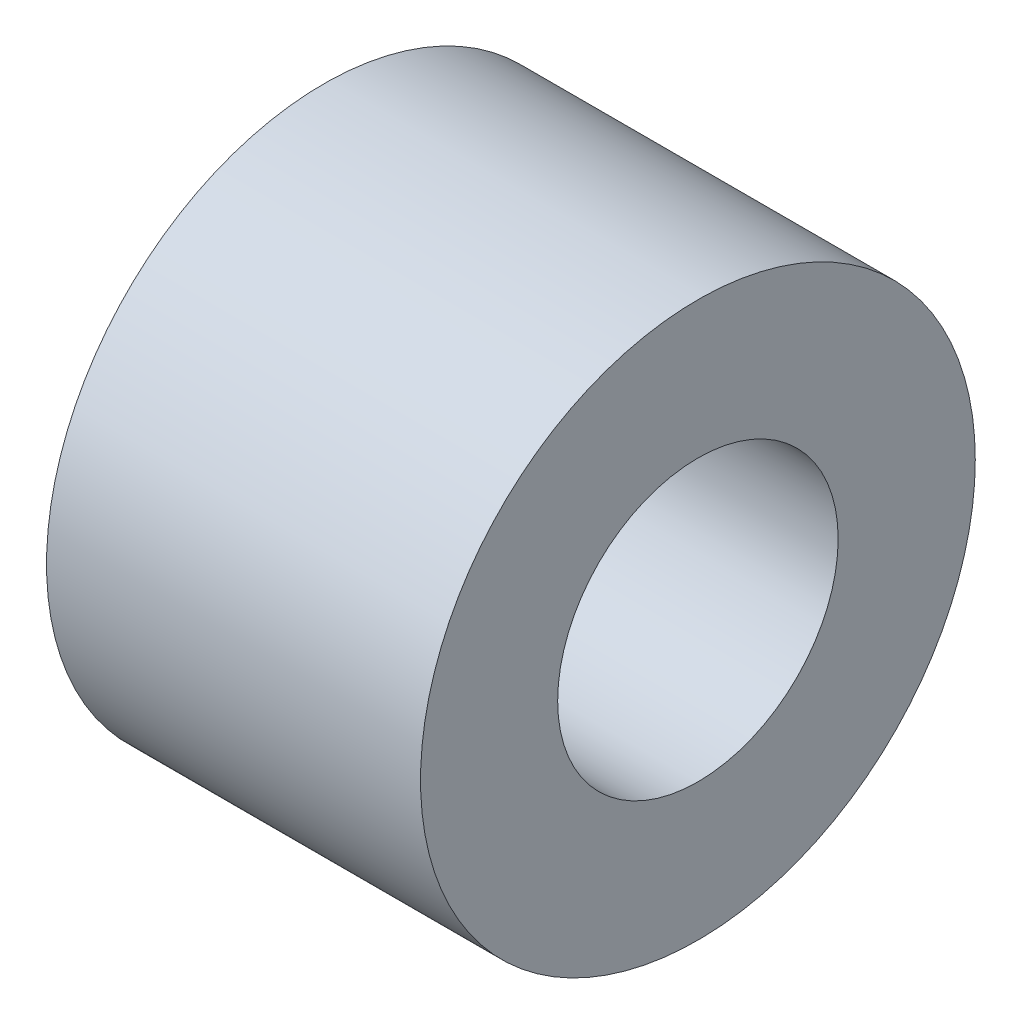
SolidWorks part; units mm, degrees
ref_plane "Front Plane" through (0, 0, 0) normal (0, 0, 1) x (1, 0, 0)
ref_plane "Top Plane" through (0, 0, 0) normal (0, 1, 0) x (1, 0, 0)
ref_plane "Right Plane" through (0, 0, 0) normal (1, 0, 0) x (0, 0, -1)
sketch "Sketch1" plane through (0, 0, 0) normal (1, 0, 0) x (0, 0, -1)
  circle A0 centre (0, 0) radius 22.25
  circle A1 centre (0, 0) radius 11.25
  dimension "D1" = 44.5
  dimension "D2" = 22.5
extrude "Boss-Extrude1" add sketch "Sketch1" along normal blind 30
